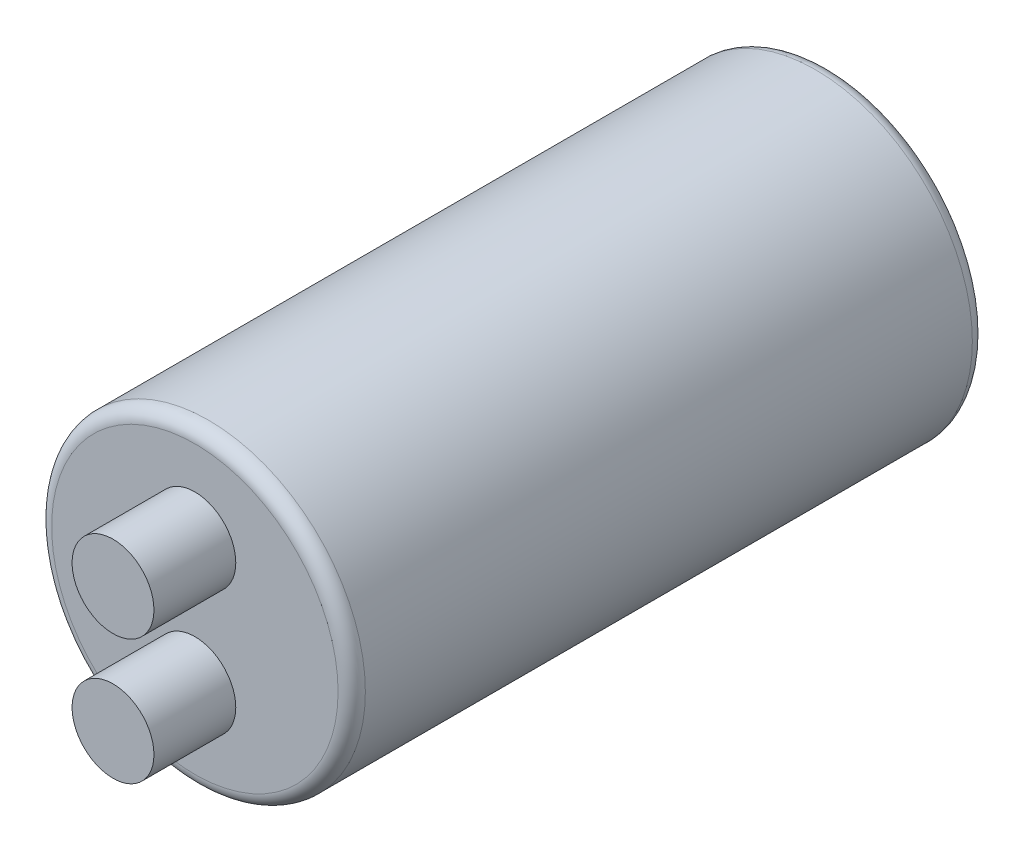
SolidWorks part; units mm, degrees
ref_plane "Front" through (0, 0, 0) normal (0, 0, 1) x (1, 0, 0)
ref_plane "Top" through (0, 0, 0) normal (0, 1, 0) x (1, 0, 0)
ref_plane "Right" through (0, 0, 0) normal (1, 0, 0) x (0, 0, -1)
sketch "Sketch1" plane through (0, 0, 0) normal (0, 0, 1) x (1, 0, 0)
  circle A0 centre (0, 0) radius 11.5
  dimension "D1" = 23
extrude "Boss-Extrude1" add sketch "Sketch1" along normal blind 46.5
fillet "Fillet1" radius 1 2 edges at (11.5, 0, 46.5) (11.5, 0, 0)
sketch "Sketch2" plane through (0, 0, 46.5) normal (0, 0, 1) x (1, 0, 0)
  line L0 (0, 0) -> (0, -7.0018) construction
  circle A0 centre (0, -4.7445) radius 3
  circle A1 centre (0, 4.4418) radius 3
  dimension "D1" = 6
  dimension "D2" = 6
extrude "Boss-Extrude2" add sketch "Sketch2" along normal blind 6
